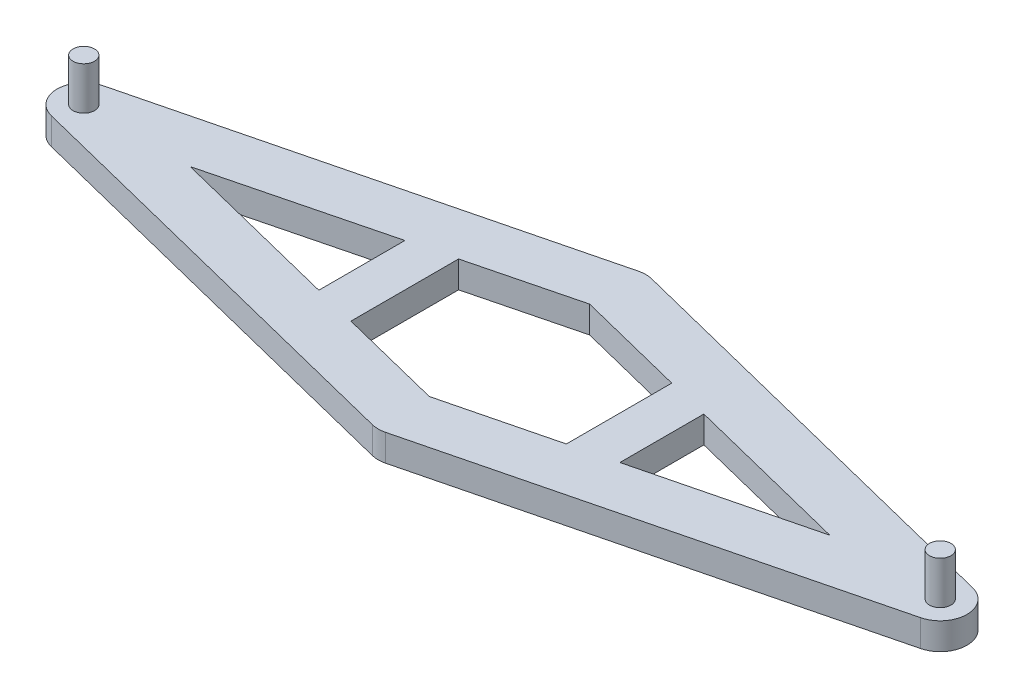
SolidWorks part; units mm, degrees
ref_plane "Front Plane" through (0, 0, 0) normal (0, 0, 1) x (1, 0, 0)
ref_plane "Top Plane" through (0, 0, 0) normal (0, 1, 0) x (1, 0, 0)
ref_plane "Right Plane" through (0, 0, 0) normal (1, 0, 0) x (0, 0, -1)
sketch "Base" plane through (0, 0, 0) normal (0, 1, 0) x (1, 0, 0)
  line L0 (-51.5701, 3.0802) -> (-0.7701, 15.7802)
  line L5 (-0.3074, -9.5041) -> (37.7091, 0)
  line L7 (0.7701, 15.7802) -> (51.5701, 3.0802)
  line L8 (-51.5701, -3.0802) -> (-0.7701, -15.7802)
  line L9 (51.5701, -3.0802) -> (0.7701, -15.7802)
  line L10 (-38.1111, -0.0652) -> (-0.2945, 9.5009)
  line L11 (-0.2945, 9.5009) -> (37.7091, 0)
  line L13 (-0.3074, -9.5041) -> (-38.1111, -0.0652)
  arc A0 (-51.5701, 3.0802) -> (-51.5701, -3.0802) centre (-50.8, 0) ccw
  arc A1 (0.7701, 15.7802) -> (-0.7701, 15.7802) centre (0, 12.7) ccw
  arc A2 (51.5701, -3.0802) -> (51.5701, 3.0802) centre (50.8, 0) ccw
  arc A3 (-0.7701, -15.7802) -> (0.7701, -15.7802) centre (0, -12.7) ccw
  circle A4 centre (-50.8, 0) radius 1.27
  circle A5 centre (50.8, 0) radius 1.27
  point P0 (0, 0)
  point P3 (-38.1111, -0.0652)
  dimension "D3" = 6.35
  dimension "D6" = 6.35
  dimension "D1" = 2.54
  dimension "D2" = 2.54
sketch "Sketch2" plane through (0, 0, 0) normal (0, 1, 0) x (1, 0, 0)
  line L0 (-51.5701, 3.0802) -> (-0.7701, 15.7802)
  line L1 (0.7701, 15.7802) -> (51.5701, 3.0802)
  line L2 (-51.5701, -3.0802) -> (-0.7701, -15.7802)
  line L3 (51.5701, -3.0802) -> (0.7701, -15.7802)
  line L4 (37.7091, 0) -> (-0.3074, -9.5041)
  line L5 (-0.3074, -9.5041) -> (-38.1111, -0.0652)
  line L6 (-38.1111, -0.0652) -> (-0.2945, 9.5009)
  line L7 (-0.2945, 9.5009) -> (37.7091, 0)
  arc A0 (-51.5701, 3.0802) -> (-51.5701, -3.0802) centre (-50.8, 0) ccw
  arc A1 (0.7701, 15.7802) -> (-0.7701, 15.7802) centre (0, 12.7) ccw
  arc A2 (51.5701, -3.0802) -> (51.5701, 3.0802) centre (50.8, 0) ccw
  arc A3 (-0.7701, -15.7802) -> (0.7701, -15.7802) centre (0, -12.7) ccw
extrude "Boss-Extrude1" add sketch "Sketch2" along normal blind 3.175
sketch "Sketch4" plane through (0, 3.175, 0) normal (0, 1, 0) x (1, 0, 0)
  line L0 (0, 12.7) -> (-50.8, 0)
  line L1 (-50.8, 0) -> (0, -12.7)
  line L2 (0, -12.7) -> (50.8, 0)
  line L3 (50.8, 0) -> (0, 12.7)
  line L4 (-17.78, 8.255) -> (-17.78, -8.255)
  line L5 (17.78, -8.255) -> (17.78, 8.255)
  line L14 (17.78, -8.255) -> (17.78, 8.255)
  line L19 (17.78, -8.255) -> (12.7, -8.255)
  line L20 (17.78, 8.255) -> (12.7, 8.255)
  line L21 (12.7, -8.255) -> (12.7, 8.255)
  line L22 (-17.78, -8.255) -> (-17.78, 8.255)
  line L23 (-17.78, -8.255) -> (-12.7, -8.255)
  line L24 (-17.78, 8.255) -> (-12.7, 8.255)
  line L25 (-12.7, -8.255) -> (-12.7, 8.255)
  circle A0 centre (-50.8, 0) radius 1.27
  circle A1 centre (50.8, 0) radius 1.27
  circle A4 centre (0, 0) radius 12.7
  point P9 (-17.78, 8.255)
  point P10 (17.78, 8.255)
  point P12 (17.78, -8.255)
  point P15 (-17.78, -8.255)
  dimension "D1" = 2.54
  dimension "D2" = 2.54
  dimension "D3" = 17.78
  dimension "D4" = 17.78
  dimension "D5" = 17.78
  dimension "D7" = 5.08
  dimension "D6" = 17.78
  dimension "D8" = 5.08
sketch "Sketch5" plane through (0, 3.175, 0) normal (0, 1, 0) x (1, 0, 0)
  circle A0 centre (-50.8, 0) radius 1.27
extrude "Boss-Extrude2" add sketch "Sketch5" along normal blind 5.08
sketch "Sketch6" plane through (0, 3.175, 0) normal (0, 1, 0) x (1, 0, 0)
  circle A0 centre (50.8, 0) radius 1.27
extrude "Boss-Extrude3" add sketch "Sketch6" along normal blind 5.08
sketch "Sketch10" plane through (0, 3.175, 0) normal (0, 1, 0) x (1, 0, 0)
  line L0 (-17.78, 8.255) -> (-17.78, -8.255)
  line L1 (17.78, -8.255) -> (17.78, 8.255)
  line L2 (17.78, -8.255) -> (12.7, -8.255)
  line L3 (17.78, 8.255) -> (12.7, 8.255)
  line L4 (12.7, -8.255) -> (12.7, 8.255)
  line L5 (-17.78, -8.255) -> (-12.7, -8.255)
  line L6 (-17.78, 8.255) -> (-12.7, 8.255)
  line L7 (-12.7, -8.255) -> (-12.7, 8.255)
extrude "Boss-Extrude6" add sketch "Sketch10" against normal up to surface (3.175 mm away) up to plane "Top Plane"
